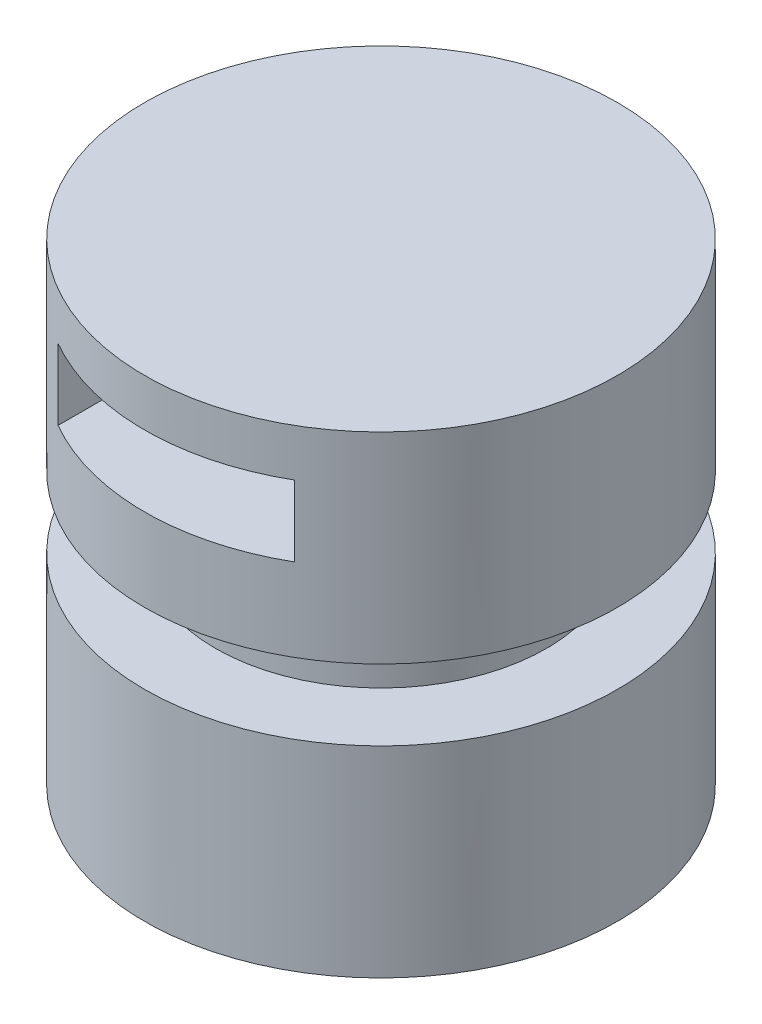
SolidWorks part; units mm, degrees
ref_plane "Front Plane" through (0, 0, 0) normal (0, 0, 1) x (1, 0, 0)
ref_plane "Top Plane" through (0, 0, 0) normal (0, 1, 0) x (1, 0, 0)
ref_plane "Right Plane" through (0, 0, 0) normal (1, 0, 0) x (0, 0, -1)
sketch "Sketch1" plane through (0, 0, 0) normal (0, 0, 1) x (1, 0, 0)
  line L1 (0, 0) -> (100, 0)
  line L2 (0, 0) -> (0, 200)
  line L3 (0, 200) -> (100, 200)
  line L4 (100, 0) -> (100, 200)
  line L5 (0, 0) -> (100, 200) construction
  line L6 (0, 200) -> (100, 0) construction
  point P0 (0, 0)
  point P5 (0, 0)
  point P6 (0, 0)
  point P7 (0, 0)
  point P8 (0, 0)
  point P9 (0, 0)
  point P10 (0, 0)
  point P12 (63.6941, 113.9631)
  point P13 (56.677, 0)
  point P14 (-7.6465, 118.0136)
  point P15 (56.677, 144.2974)
  point P16 (0, 144.2974)
  point P17 (0, 0)
  point P18 (0, 0)
  dimension "D1" = 100
  dimension "D2" = 200
revolve "Revolve1" add sketch "Sketch1" angle 360 about L2
sketch "Sketch3" plane through (0, 0, 0) normal (1, 0, 0) x (0, 0, -1)
  line L0 (0, 200) -> (0, 0) construction
  line L1 (70, 115) -> (100, 115)
  line L2 (70, 115) -> (70, 85)
  line L3 (70, 85) -> (100, 85)
  line L4 (100, 115) -> (100, 85)
  line L5 (70, 115) -> (100, 85) construction
  line L6 (70, 85) -> (100, 115) construction
  line L7 (100, 200) -> (-100, 200) construction
  line L8 (100, 0) -> (100, 200) construction
  line L9 (70, 100) -> (100, 100) construction
  point P0 (85, 100)
  point P14 (0, 0)
  point P15 (0, 0)
  dimension "D1" = 30
  dimension "D2" = 100
revolve "Cut-Revolve1" cut sketch "Sketch3" angle 360 about L0
sketch "Sketch4" plane through (0, 0, 0) normal (0, 0, 1) x (1, 0, 0)
  line L0 (100, 200) -> (-100, 200) construction
  line L1 (-50, 180) -> (50, 180)
  line L2 (-50, 180) -> (-50, 150)
  line L3 (-50, 150) -> (50, 150)
  line L4 (50, 180) -> (50, 150)
  line L5 (0, 150) -> (0, 200) construction
  dimension "D1" = 100
  dimension "D2" = 30
  dimension "D3" = 20
extrude "Cut-Extrude1" cut sketch "Sketch4" against normal through all and the other way through all
